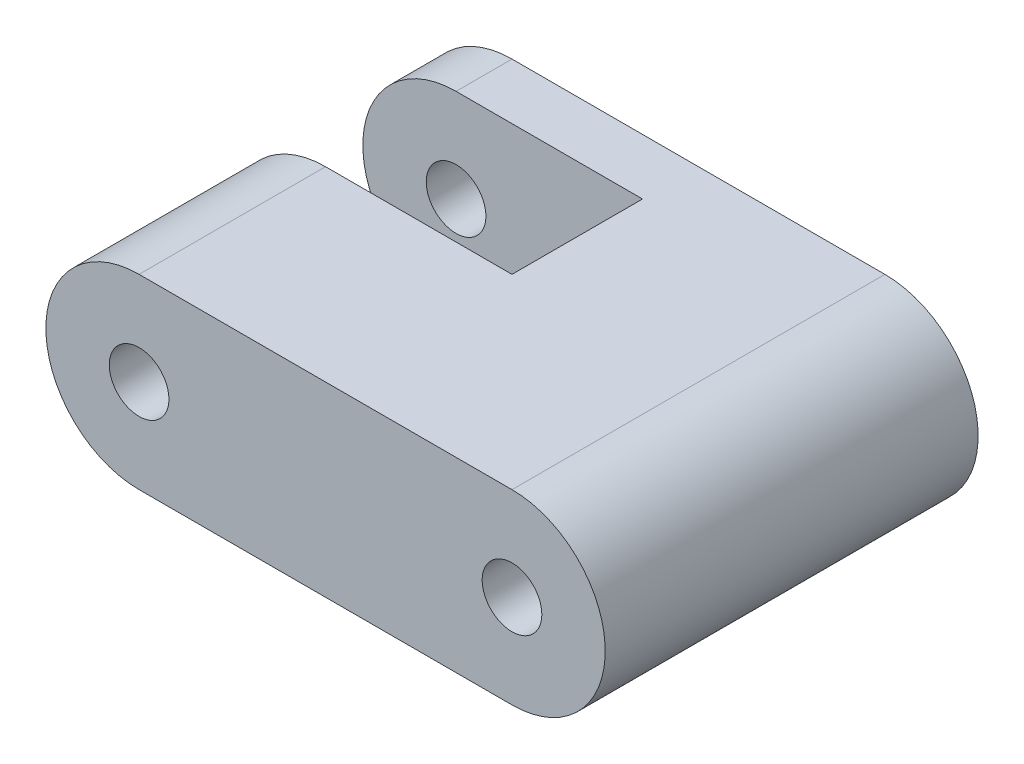
SolidWorks part; units mm, degrees
ref_plane "Front Plane" through (0, 0, 0) normal (0, 0, 1) x (1, 0, 0)
ref_plane "Top Plane" through (0, 0, 0) normal (0, 1, 0) x (1, 0, 0)
ref_plane "Right Plane" through (0, 0, 0) normal (1, 0, 0) x (0, 0, -1)
sketch "Sketch1" plane through (0, 0, 0) normal (0, 0, 1) x (1, 0, 0)
  line L0 (-20, 5) -> (0, 5)
  line L1 (-20, -5) -> (0, -5)
  arc A0 (0, -5) -> (0, 5) centre (0, 0) ccw
  arc A1 (-20, 5) -> (-20, -5) centre (-20, 0) ccw
  circle A2 centre (-20, 0) radius 1.6
  circle A3 centre (0, 0) radius 1.6
  dimension "D1" = 10
  dimension "D3" = 3.2
  dimension "D4" = 3.2
  dimension "D2" = 20
extrude "Boss-Extrude1" add sketch "Sketch1" along normal blind 20
sketch "Sketch2" plane through (0, 5, 0) normal (0, 1, 0) x (1, 0, 0)
  line L0 (-25, 0) -> (-25, -20) construction
  line L1 (-25, -3) -> (-10, -3)
  line L2 (-25, -3) -> (-25, -10)
  line L3 (-25, -10) -> (-10, -10)
  line L4 (-10, -3) -> (-10, -10)
  line L5 (0, 0) -> (-20, 0) construction
  dimension "D1" = 3
  dimension "D2" = 7
  dimension "D3" = 15
extrude "Cut-Extrude1" cut sketch "Sketch2" against normal through all
